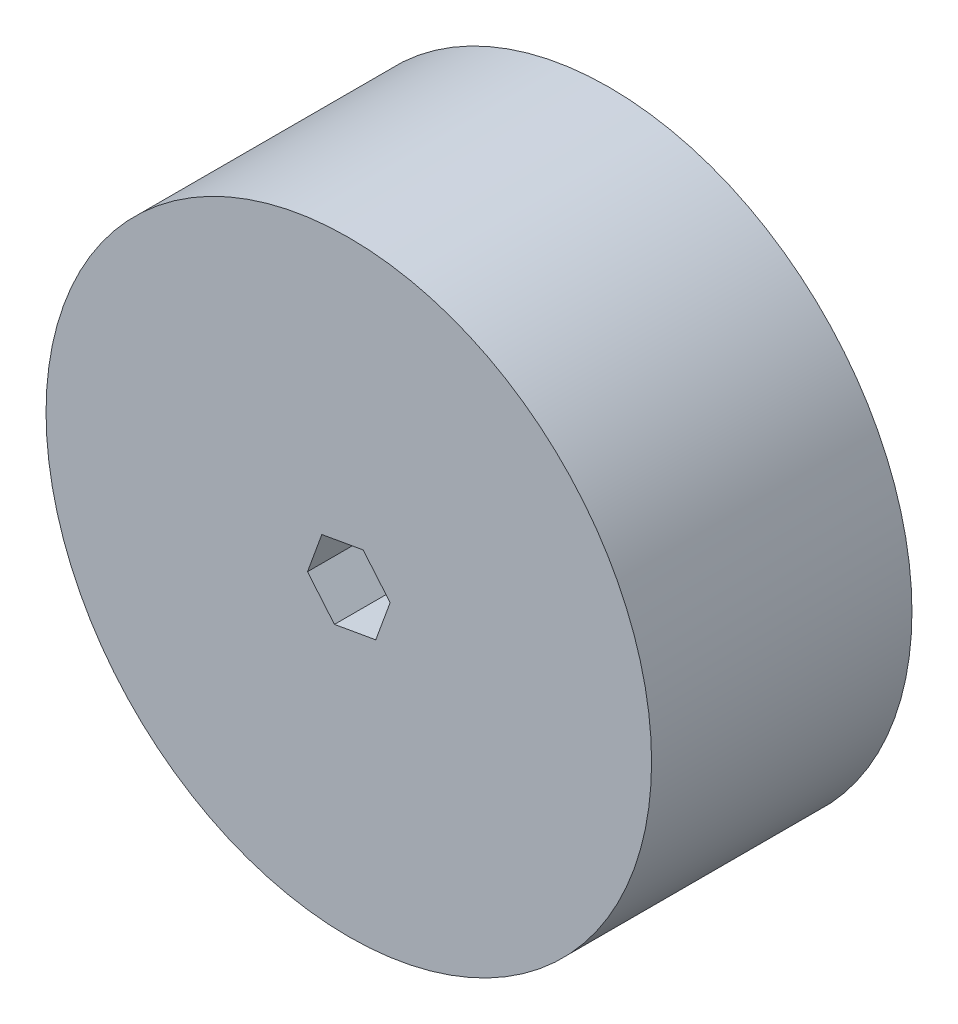
SolidWorks part; units mm, degrees
ref_plane "前视基准面" through (0, 0, 0) normal (0, 0, 1) x (1, 0, 0)
ref_plane "上视基准面" through (0, 0, 0) normal (0, 1, 0) x (1, 0, 0)
ref_plane "右视基准面" through (0, 0, 0) normal (1, 0, 0) x (0, 0, -1)
other "Configuration Table"
sketch "草图1" plane through (0, 0, 0) normal (0, 0, 1) x (1, 0, 0)
  circle A0 centre (0, 0) radius 50
  dimension "D1" = 100
extrude "凸台-拉伸1" add sketch "草图1" along normal blind 43
sketch "草图2" plane through (0, 0, 43) normal (0, 0, 1) x (1, 0, 0)
  line L1 (4.4531, -5.3075) -> (6.823, 1.2028)
  line L2 (6.823, 1.2028) -> (2.3699, 6.5103)
  line L3 (2.3699, 6.5103) -> (-4.4531, 5.3075)
  line L4 (-4.4531, 5.3075) -> (-6.823, -1.2028)
  line L5 (-6.823, -1.2028) -> (-2.3699, -6.5103)
  line L6 (-2.3699, -6.5103) -> (4.4531, -5.3075)
  circle A0 centre (0, 0) radius 6 construction
  dimension "D1" = 12
extrude "切除-拉伸1" cut sketch "草图2" against normal blind 25
